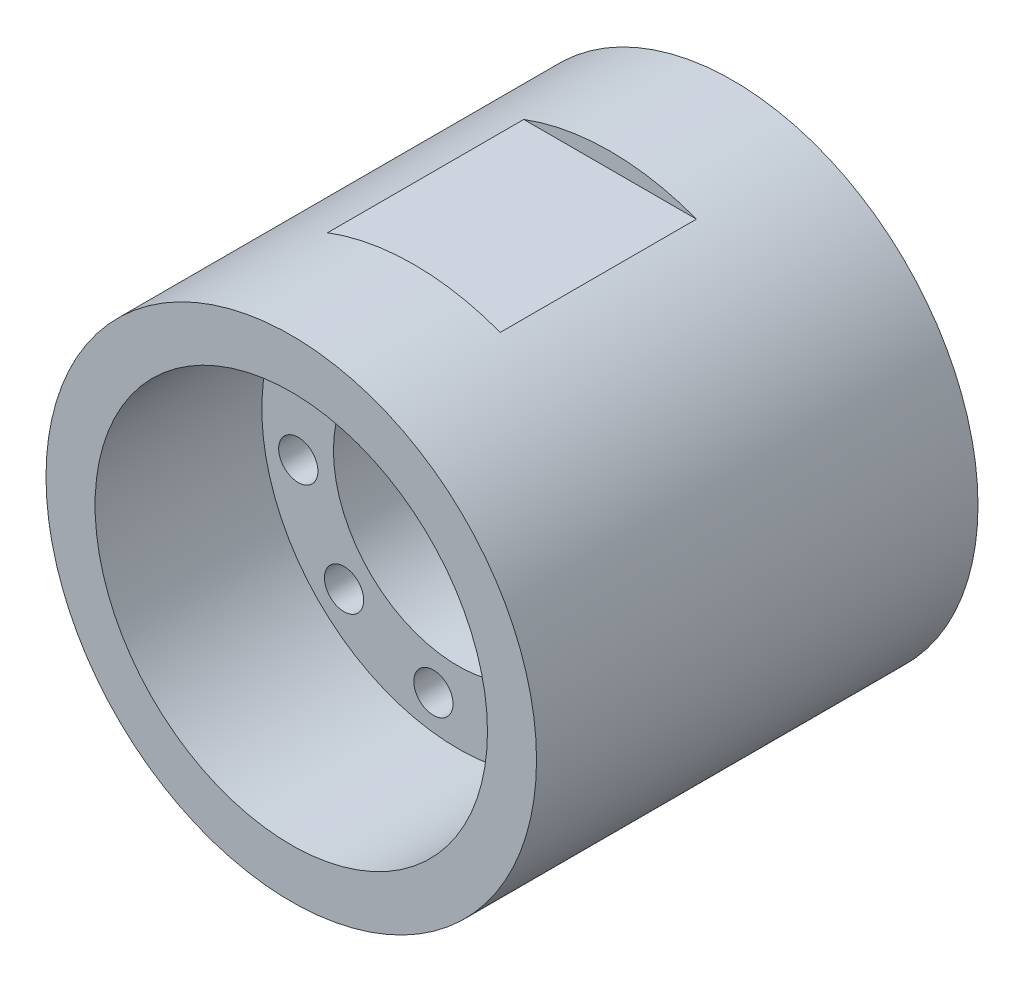
SolidWorks part; units mm, degrees
material "AISI 316 Annealed Stainless Steel Bar (SS)"
ref_plane "Front Plane" through (0, 0, 0) normal (0, 0, 1) x (1, 0, 0)
ref_plane "Top Plane" through (0, 0, 0) normal (0, 1, 0) x (1, 0, 0)
ref_plane "Right Plane" through (0, 0, 0) normal (1, 0, 0) x (0, 0, -1)
sketch "Sketch1" plane through (0, 0, 0) normal (0, 0, 1) x (1, 0, 0)
  circle A0 centre (0, 0) radius 25
  dimension "D1" = 50
extrude "Boss-Extrude1" add sketch "Sketch1" along normal blind 45
sketch "Sketch2" plane through (0, 0, 45) normal (0, 0, 1) x (1, 0, 0)
  circle A0 centre (0, 0) radius 20
  dimension "D1" = 40
extrude "Cut-Extrude1" cut sketch "Sketch2" against normal blind 17
sketch "Sketch3" plane through (0, 0, 28) normal (0, 0, 1) x (1, 0, 0)
  circle A0 centre (0, 0) radius 12.7
  dimension "D1" = 25.4
extrude "Cut-Extrude2" cut sketch "Sketch3" against normal blind 18
cosmetic thread "Cosmetic Thread1" parameters "D2"=28.575
sketch "Sketch4" plane through (0, 0, 28) normal (0, 0, 1) x (1, 0, 0)
  circle A0 centre (0, 0) radius 16.5 construction
  circle A1 centre (-7.5527, 14.6699) radius 2
  dimension "D1" = 33
  dimension "D2" = 4
extrude "Cut-Extrude3" cut sketch "Sketch4" against normal through all
pattern_circular "CirPattern1" count 10 over 360 about axis through (0, 0, 0) along (0, 0, 1) of "Cut-Extrude3"
sketch "Sketch5" plane through (0, 0, 0) normal (0, 0, -1) x (-1, 0, 0)
  circle A0 centre (0, 0) radius 20
  dimension "D1" = 40
extrude "Cut-Extrude4" cut sketch "Sketch5" against normal blind 20
cosmetic thread "Cosmetic Thread2" parameters "D1"=12, "D2"=44.45
sketch "Sketch6" plane through (0, 0, 0) normal (0, 0, -1) x (-1, 0, 0)
  line L0 (-8.8, 23.4) -> (8.8, 23.4)
  line L1 (-25, 0) -> (25, 0) construction
  line L2 (-8.8, -23.4) -> (8.8, -23.4)
  arc A1 (8.8, 23.4) -> (-8.8, 23.4) centre (0, 0) ccw
  circle A2 centre (0, 0) radius 25 construction
  arc A3 (8.8, -23.4) -> (-8.8, -23.4) centre (0, 0) cw
  dimension "D1" = 23.4
ref_plane "Plane1" through (0, 0, 22.5) normal (0, 0, 1) x (1, 0, 0)
sketch "Sketch8" plane through (0, 0, 22.5) normal (0, 0, 1) x (1, 0, 0)
  line L0 (-8.8, 23.4) -> (8.8, 23.4)
  line L1 (-8.8, -23.4) -> (8.8, -23.4)
  arc A0 (8.8, 23.4) -> (-8.8, 23.4) centre (0, 0) ccw
  arc A1 (-8.8, -23.4) -> (8.8, -23.4) centre (0, 0) ccw
extrude "Cut-Extrude8" cut sketch "Sketch8" against normal mid plane 20
